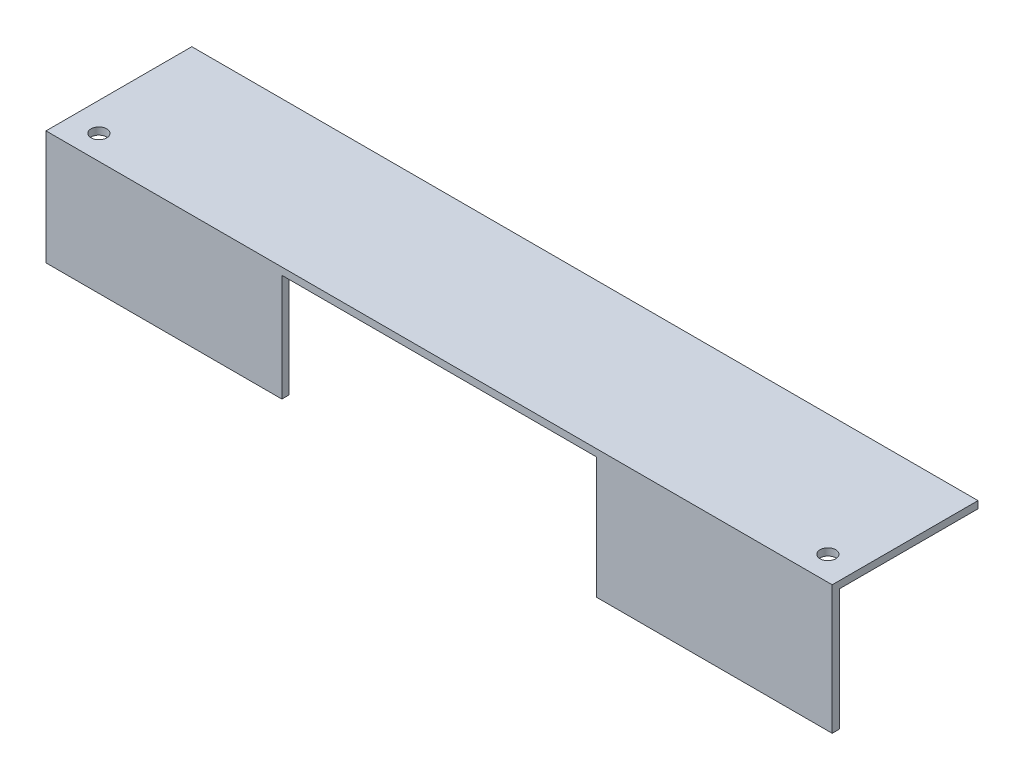
SolidWorks part; units mm, degrees
ref_plane "前视基准面" through (0, 0, 0) normal (0, 0, 1) x (1, 0, 0)
ref_plane "上视基准面" through (0, 0, 0) normal (0, 1, 0) x (1, 0, 0)
ref_plane "右视基准面" through (0, 0, 0) normal (1, 0, 0) x (0, 0, -1)
sketch "草图1" plane through (0, 0, 0) normal (0, 1, 0) x (1, 0, 0)
  line L1 (-55, 9.7) -> (55, 9.7)
  line L2 (-55, 9.7) -> (-55, -9.7)
  line L3 (-55, -9.7) -> (55, -9.7)
  line L4 (55, 9.7) -> (55, -9.7)
  line L5 (-55, 9.7) -> (55, -9.7) construction
  line L6 (-55, -9.7) -> (55, 9.7) construction
  point P0 (0, 0)
  dimension "D1" = 19.4
  dimension "D2" = 110
extrude "凸台-拉伸1" add sketch "草图1" along normal blind 1
sketch "草图2" plane through (0, 0, 9.7) normal (0, 0, 1) x (1, 0, 0)
  line L1 (55, 1) -> (22, 1)
  line L2 (55, 1) -> (55, -17)
  line L3 (55, -17) -> (22, -17)
  line L4 (22, 1) -> (22, -17)
  dimension "D1" = 18
  dimension "D2" = 33
extrude "凸台-拉伸2" add sketch "草图2" along normal blind 1
sketch "草图3" plane through (0, 0, 9.7) normal (0, 0, 1) x (1, 0, 0)
  line L1 (-55, 1) -> (-22, 1)
  line L2 (-55, 1) -> (-55, -15)
  line L3 (-55, -15) -> (-22, -15)
  line L4 (-22, 1) -> (-22, -15)
  dimension "D1" = 16
  dimension "D2" = 33
extrude "凸台-拉伸3" add sketch "草图3" along normal blind 1
sketch "草图5" plane through (0, 1, 0) normal (0, 1, 0) x (1, 0, 0)
  line L1 (-22, -9.7) -> (22, -9.7)
  line L2 (-22, -9.7) -> (-22, -10.7)
  line L3 (-22, -10.7) -> (22, -10.7)
  line L4 (22, -9.7) -> (22, -10.7)
extrude "凸台-拉伸5" add sketch "草图5" against normal blind 1
sketch "草图6" plane through (0, 1, 0) normal (0, 1, 0) x (1, 0, 0)
  line L1 (55, -10.7) -> (-55, -10.7) construction
  line L2 (55, -10.7) -> (55, 9.7) construction
  circle A0 centre (51, -7.3) radius 1.1
  dimension "D1" = 3.4
  dimension "D3" = 2.2
  dimension "D2" = 4
extrude "切除-拉伸1" cut sketch "草图6" against normal blind 10
mirror "镜向1" about plane through (0, 0, 0) normal (1, 0, 0) of "切除-拉伸1"
equation "\"1。2\"=1"
